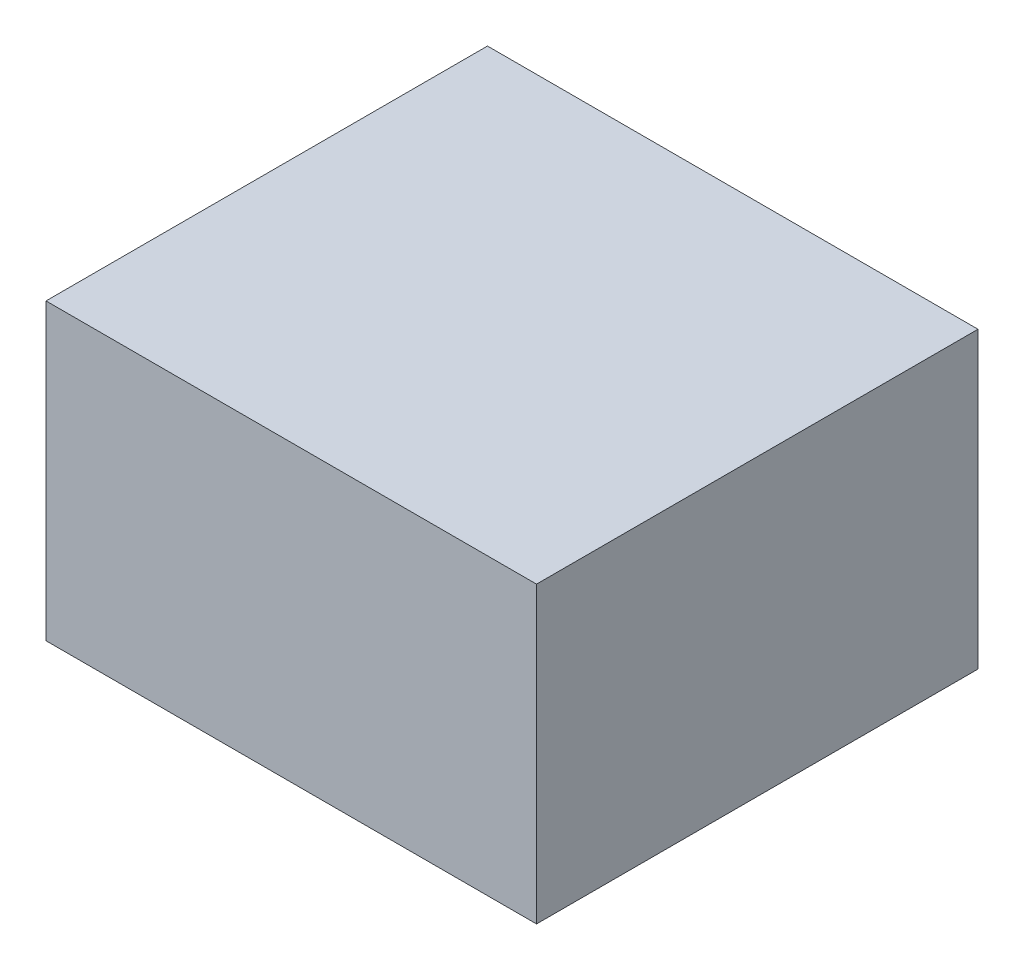
SolidWorks part; units mm, degrees
ref_plane "Front Plane" through (0, 0, 0) normal (0, 0, 1) x (1, 0, 0)
ref_plane "Top Plane" through (0, 0, 0) normal (0, 1, 0) x (1, 0, 0)
ref_plane "Right Plane" through (0, 0, 0) normal (1, 0, 0) x (0, 0, -1)
sketch "Sketch1" plane through (0, 0, 0) normal (0, 0, 1) x (1, 0, 0)
  line L0 (0, 0) -> (100, 0)
  line L1 (100, 0) -> (100, 60)
  line L2 (100, 60) -> (0, 60)
  line L3 (0, 60) -> (0, 0)
  dimension "D1" = 60
  dimension "D2" = 100
extrude "Boss-Extrude1" add sketch "Sketch1" along normal blind 90
